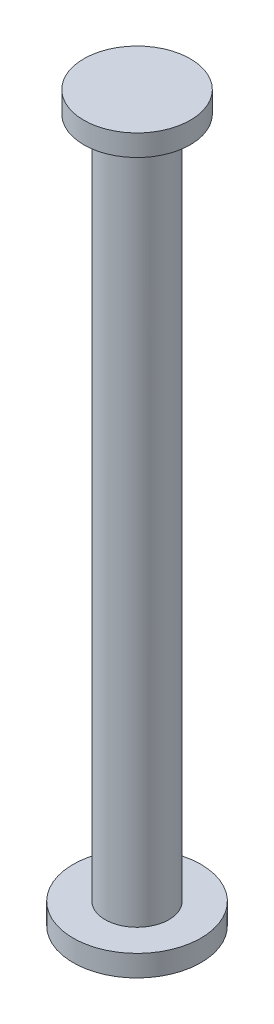
SolidWorks part; units mm, degrees
ref_plane "Alzado" through (0, 0, 0) normal (0, 0, 1) x (1, 0, 0)
ref_plane "Planta" through (0, 0, 0) normal (0, 1, 0) x (1, 0, 0)
ref_plane "Vista lateral" through (0, 0, 0) normal (1, 0, 0) x (0, 0, -1)
sketch "Croquis1" plane through (0, 0, 0) normal (0, 1, 0) x (1, 0, 0)
  circle A0 centre (0, 0) radius 75
  dimension "D1" = 150
extrude "Saliente-Extruir1" add sketch "Croquis1" along normal blind 1600
sketch "Croquis2" plane through (0, 1600, 0) normal (0, 1, 0) x (1, 0, 0)
  circle A0 centre (0, 0) radius 125
  dimension "D1" = 250
extrude "Saliente-Extruir2" add sketch "Croquis2" along normal blind 50
sketch "Croquis3" plane through (0, 0, 0) normal (0, -1, 0) x (1, 0, 0)
  circle A0 centre (0, 0) radius 150
  dimension "D1" = 300
extrude "Saliente-Extruir3" add sketch "Croquis3" along normal blind 50
sketch "Croquis4" plane through (0, -50, 0) normal (0, -1, 0) x (1, 0, 0)
  line L0 (0, 150) -> (0, -150) construction
  line L1 (-100, 5) -> (-30, 5)
  line L2 (-100, 5) -> (-100, -15)
  line L3 (-100, -15) -> (-30, -15)
  line L4 (-30, 5) -> (-30, -15)
  line L5 (30, 5) -> (30, -15)
  line L6 (100, -15) -> (30, -15)
  line L7 (100, 5) -> (100, -15)
  line L8 (100, 5) -> (30, 5)
  circle A0 centre (0, 0) radius 150 construction
  dimension "D1" = 70
  dimension "D2" = 20
  dimension "D3" = 15
  dimension "D4" = 100
extrude "Cortar-Extruir1" cut sketch "Croquis4" against normal blind 30
